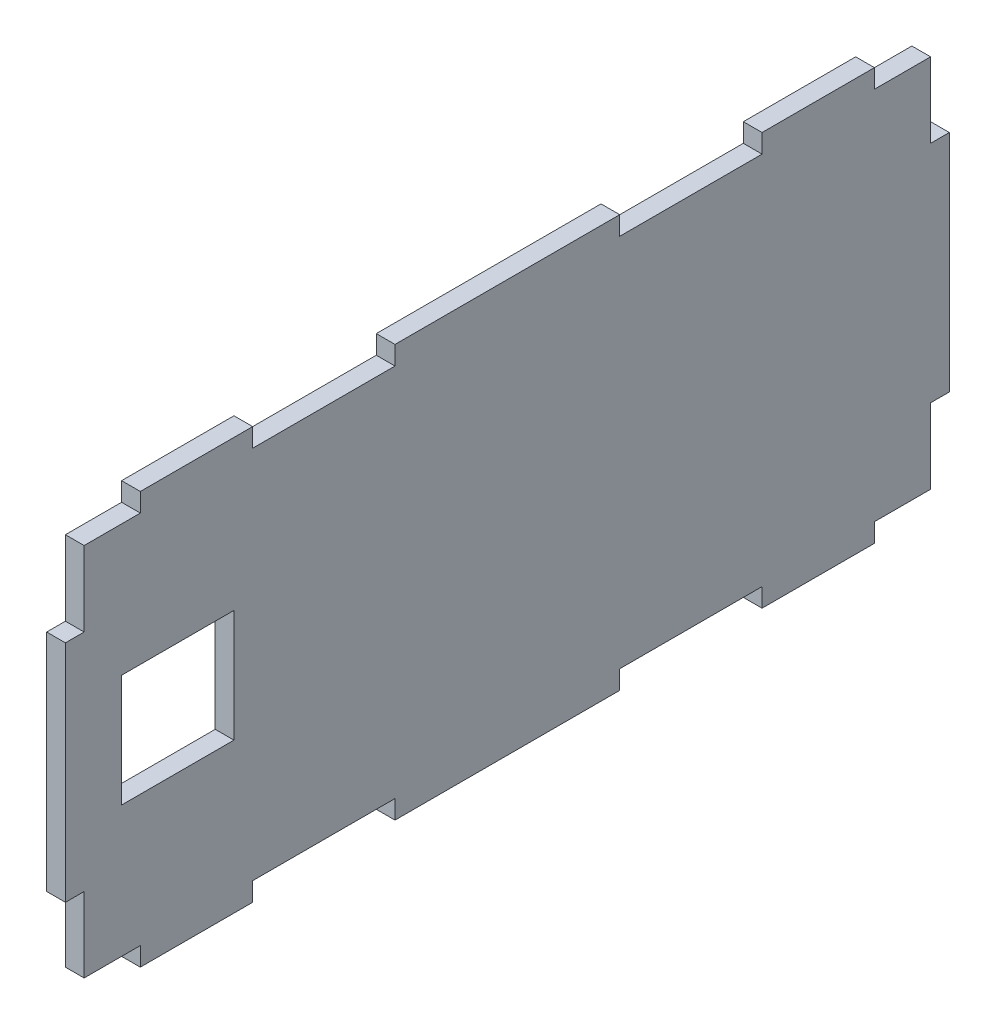
SolidWorks part; units mm, degrees
ref_plane "Front Plane" through (0, 0, 0) normal (0, 0, 1) x (1, 0, 0)
ref_plane "Top Plane" through (0, 0, 0) normal (0, 1, 0) x (1, 0, 0)
ref_plane "Right Plane" through (0, 0, 0) normal (1, 0, 0) x (0, 0, -1)
sketch "Sketch1" plane through (0, 0, 0) normal (1, 0, 0) x (0, 0, -1)
  line L0 (-113, 0) -> (113, 0) construction
  line L1 (113, -50) -> (-113, -50)
  line L2 (113, -50) -> (113, 50)
  line L3 (113, 50) -> (-113, 50)
  line L4 (-113, -50) -> (-113, 50)
  line L5 (113, -50) -> (-113, 50) construction
  line L6 (113, 50) -> (-113, -50) construction
  line L7 (0, -50) -> (0, 50) construction
  line L8 (113, -30) -> (118, -30)
  line L9 (98, 50) -> (68, 50)
  line L10 (98, 50) -> (98, 55)
  line L11 (98, 55) -> (68, 55)
  line L12 (68, 50) -> (68, 55)
  line L13 (0, 50) -> (30, 50)
  line L14 (0, 50) -> (0, 55)
  line L15 (-30, 55) -> (30, 55)
  line L16 (30, 50) -> (30, 55)
  line L17 (113, 0) -> (118, 0)
  line L18 (113, 0) -> (113, 30)
  line L19 (113, 30) -> (118, 30)
  line L20 (118, -30) -> (118, 30)
  line L21 (98, -50) -> (98, -55)
  line L22 (68, -50) -> (68, -55)
  line L23 (98, -55) -> (68, -55)
  line L24 (30, -50) -> (30, -55)
  line L25 (-30, -55) -> (30, -55)
  line L26 (-30, -50) -> (-30, -55)
  line L27 (-68, -50) -> (-68, -55)
  line L28 (-98, -50) -> (-98, -55)
  line L29 (-98, -55) -> (-68, -55)
  line L30 (-113, -30) -> (-118, -30)
  line L31 (-118, -30) -> (-118, 30)
  line L32 (-113, 30) -> (-118, 30)
  line L33 (-98, 50) -> (-98, 55)
  line L34 (-68, 50) -> (-68, 55)
  line L35 (-98, 55) -> (-68, 55)
  line L36 (-30, 50) -> (-30, 55)
  line L37 (30, 50) -> (-30, 50)
  line L38 (-68, 50) -> (-98, 50)
  line L39 (-113, 30) -> (-113, -30)
  line L40 (-98, -50) -> (-68, -50)
  line L41 (-30, -50) -> (30, -50)
  line L42 (68, -50) -> (98, -50)
  line L43 (113, -30) -> (113, 30)
  line L44 (98, 50) -> (68, 50)
  line L46 (-103, -15) -> (-73, -15)
  line L47 (-103, -15) -> (-103, 15)
  line L48 (-103, 15) -> (-73, 15)
  line L49 (-73, -15) -> (-73, 15)
  point P0 (0, 0)
  point P17 (98, 52.5)
  point P32 (0, -55)
  dimension "D1" = 226
  dimension "D2" = 100
  dimension "D3" = 5
  dimension "D4" = 5
  dimension "D5" = 15
  dimension "D6" = 30
  dimension "D7" = 30
  dimension "D8" = 5
  dimension "D9" = 30
  dimension "D10" = 10
  dimension "D11" = 30
  dimension "D12" = 35
  dimension "D13" = 35
  dimension "D14" = 30
extrude "Boss-Extrude1" add sketch "Sketch1" along normal blind 5 contours L4 L1 L2 L3 | L35 L33 L3 L34 | L28 L29 L27 L1 | L4 L32 L31 L30 | L12 L3 L10 L11 | L37 L36 L15 L16 | L25 L24 L41 L26 | L23 L22 L42 L21 | L43 L8 L20 L19
